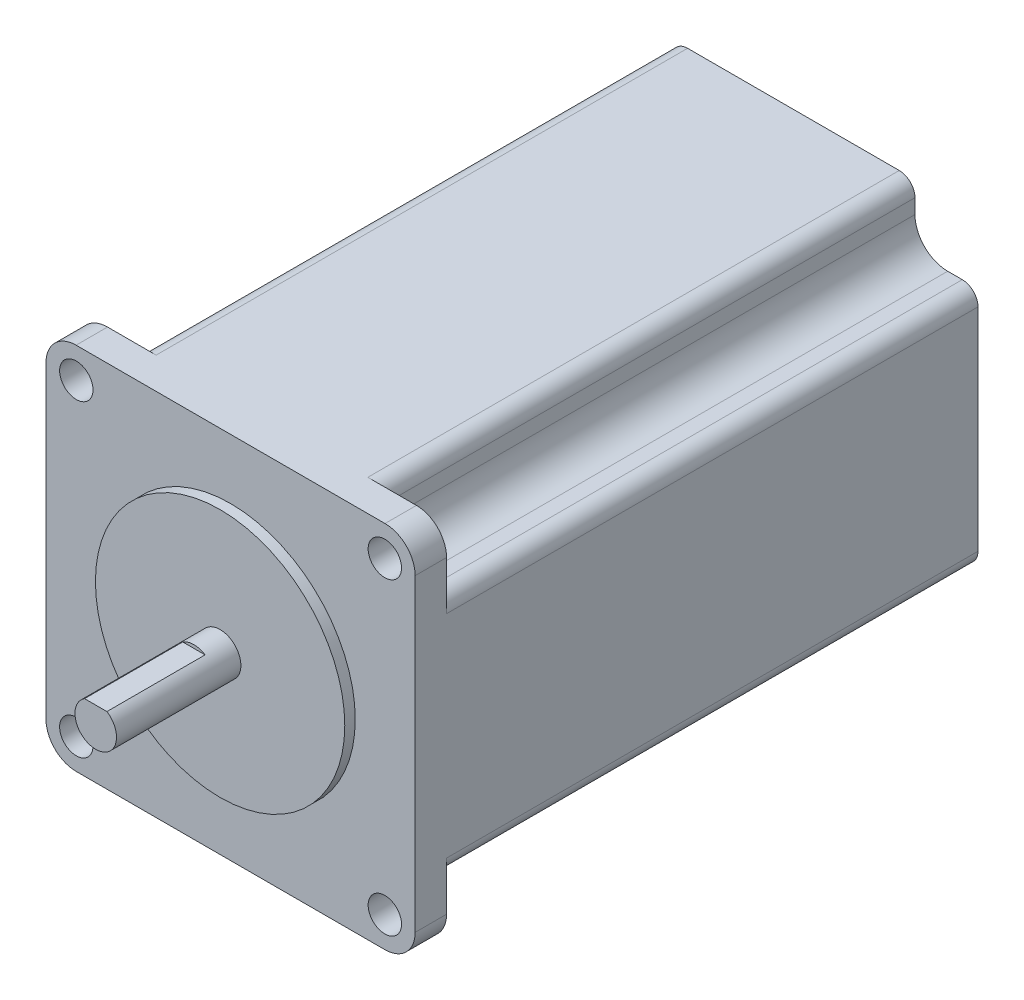
SolidWorks part; units mm, degrees
ref_plane "Front Plane" through (0, 0, 0) normal (0, 0, 1) x (1, 0, 0)
ref_plane "Top Plane" through (0, 0, 0) normal (0, 1, 0) x (1, 0, 0)
ref_plane "Right Plane" through (0, 0, 0) normal (1, 0, 0) x (0, 0, -1)
sketch "Sketch1" plane through (0, 0, 0) normal (0, 0, 1) x (1, 0, 0)
  line L1 (-28.2, 28.2) -> (28.2, 28.2)
  line L2 (-28.2, 28.2) -> (-28.2, -28.2)
  line L3 (-28.2, -28.2) -> (28.2, -28.2)
  line L4 (28.2, 28.2) -> (28.2, -28.2)
  line L5 (-28.2, 28.2) -> (28.2, -28.2) construction
  line L6 (-28.2, -28.2) -> (28.2, 28.2) construction
  point P0 (0, 0)
  dimension "D1" = 56.4
  dimension "D2" = 56.4
extrude "Boss-Extrude1" add sketch "Sketch1" against normal blind 86
sketch "Sketch2" plane through (0, 0, -86) normal (0, 0, -1) x (-1, 0, 0)
  line L0 (28.2, 28.2) -> (28.2, 18.57)
  line L1 (-28.2, 28.2) -> (-18.57, 28.2)
  line L2 (-28.2, 28.2) -> (-28.2, 18.57)
  line L3 (-28.2, 18.57) -> (-18.57, 18.57)
  line L4 (-18.57, 28.2) -> (-18.57, 18.57)
  line L5 (28.2, 28.2) -> (18.57, 28.2)
  line L6 (18.57, 28.2) -> (18.57, 18.57)
  line L7 (28.2, 18.57) -> (18.57, 18.57)
  line L8 (28.2, -28.2) -> (18.57, -28.2)
  line L9 (28.2, -28.2) -> (28.2, -18.57)
  line L10 (28.2, -18.57) -> (18.57, -18.57)
  line L11 (18.57, -28.2) -> (18.57, -18.57)
  line L12 (-28.2, -28.2) -> (-28.2, -18.57)
  line L13 (-28.2, -28.2) -> (-18.57, -28.2)
  line L14 (-18.57, -28.2) -> (-18.57, -18.57)
  line L15 (-28.2, -18.57) -> (-18.57, -18.57)
  point P20 (0, 0)
  dimension "D1" = 9.63
  dimension "D2" = 9.63
  dimension "D3" = 4
extrude "Cut-Extrude1" cut sketch "Sketch2" against normal blind 81.2
fillet "Fillet1" radius 5 4 edges at (18.57, -18.57, -45.4) (-18.57, -18.57, -45.4) (-18.57, 18.57, -45.4) (18.57, 18.57, -45.4)
fillet "Fillet2" radius 2.4 8 edges at (28.2, -18.57, -45.4) (28.2, 18.57, -45.4) (18.57, 28.2, -45.4) (-18.57, 28.2, -45.4) (-28.2, 18.57, -45.4) (-28.2, -18.57, -45.4) (-18.57, -28.2, -45.4) (18.57, -28.2, -45.4)
fillet "Fillet3" radius 4.6 4 edges at (28.2, -28.2, -2.4) (28.2, 28.2, -2.4) (-28.2, -28.2, -2.4) (-28.2, 28.2, -2.4)
sketch "Sketch3" plane through (0, 0, 0) normal (0, 0, 1) x (1, 0, 0)
  line L0 (-23.57, 28.2) -> (-23.57, 23.57)
  line L1 (23.6, 28.2) -> (-23.6, 28.2) construction
  line L2 (-23.57, 23.57) -> (-28.2, 23.57)
  line L3 (-28.2, 23.6) -> (-28.2, -23.6) construction
  line L5 (0, 28.2) -> (0, -28.2) construction
  line L6 (-23.6, -28.2) -> (23.6, -28.2) construction
  line L8 (-28.2, 0) -> (28.2, 0) construction
  line L9 (28.2, -23.6) -> (28.2, 23.6) construction
  point P96 (0, 0)
  point P219 (0, 0)
  dimension "D1" = 4.63
  dimension "D2" = 4.63
hole_wizard "Ø5.1 (5.1) Diameter Hole1" positions "Sketch4" profile "Sketch5" hole size "Ø5.1" standard "ANSI Metric" end condition through all
sketch "Sketch4" plane through (0, 0, 0) normal (0, 0, 1) x (1, 0, 0)
  point P0 (-23.57, 23.57)
sketch "Sketch5" plane through (-23.57, 23.57, 0) normal (1, 0, 0) x (0, -1, 0)
  line L0 (0, 0) -> (0, 86)
  line L1 (0, 86) -> (2.55, 86)
  line L2 (2.55, 86) -> (2.55, 0)
  line L5 (2.55, 0) -> (0, 0)
  line L11 (0, -6.35) -> (0, 107.95) construction
  dimension "Thru Hole Dia." = 5.1
  dimension "Thru Hole Depth" = 86
sketch "Sketch6" plane through (0, 0, 0) normal (0, 1, 0) x (1, 0, 0)
  line L0 (0, 0) -> (0, 86) construction
  line L1 (16.17, 86) -> (-16.17, 86) construction
pattern_circular "CirPattern1" count 4 over 360 about axis through (0, 0, 0) along (0, 0, 1) of "Ø5.1 (5.1) Diameter Hole1"
sketch "Sketch7" plane through (0, 0, 0) normal (0, 0, 1) x (1, 0, 0)
  circle A0 centre (0, 0) radius 19.05
  dimension "D1" = 38.1
extrude "Boss-Extrude2" add sketch "Sketch7" along normal blind 1.6
sketch "Sketch8" plane through (0, 0, 1.6) normal (0, 0, 1) x (1, 0, 0)
  circle A0 centre (0, 0) radius 3.175
  dimension "D1" = 6.35
extrude "Boss-Extrude3" add sketch "Sketch8" along normal blind 19
sketch "Sketch9" plane through (0, 0, 20.6) normal (0, 0, 1) x (1, 0, 0)
  line L0 (-1.71, 2.6752) -> (1.71, 2.6752)
  arc A0 (1.71, 2.6752) -> (-1.71, 2.6752) centre (0, 0) ccw
  dimension "D2" = 3.175
  dimension "D1" = 3.42
extrude "Cut-Extrude2" cut sketch "Sketch9" against normal blind 15
sketch "Sketch11" plane through (0, -28.2, 0) normal (0, -1, 0) x (1, 0, 0)
  line L0 (16.17, -86) -> (16.17, -4.8) construction
  line L1 (-16.17, -86) -> (16.17, -86)
  line L2 (-16.17, -86) -> (-16.17, -66)
  line L3 (-16.17, -66) -> (16.17, -66)
  line L4 (16.17, -86) -> (16.17, -66)
  line L5 (-16.17, -4.8) -> (-16.17, -86) construction
  line L6 (16.17, -4.8) -> (-16.17, -4.8)
  line L7 (16.17, -4.8) -> (16.17, -24.8)
  line L8 (16.17, -24.8) -> (-16.17, -24.8)
  line L9 (-16.17, -4.8) -> (-16.17, -24.8)
  dimension "D1" = 20
  dimension "D2" = 20
extrude "Boss-Extrude4" add sketch "Sketch11" along normal blind 0.2
